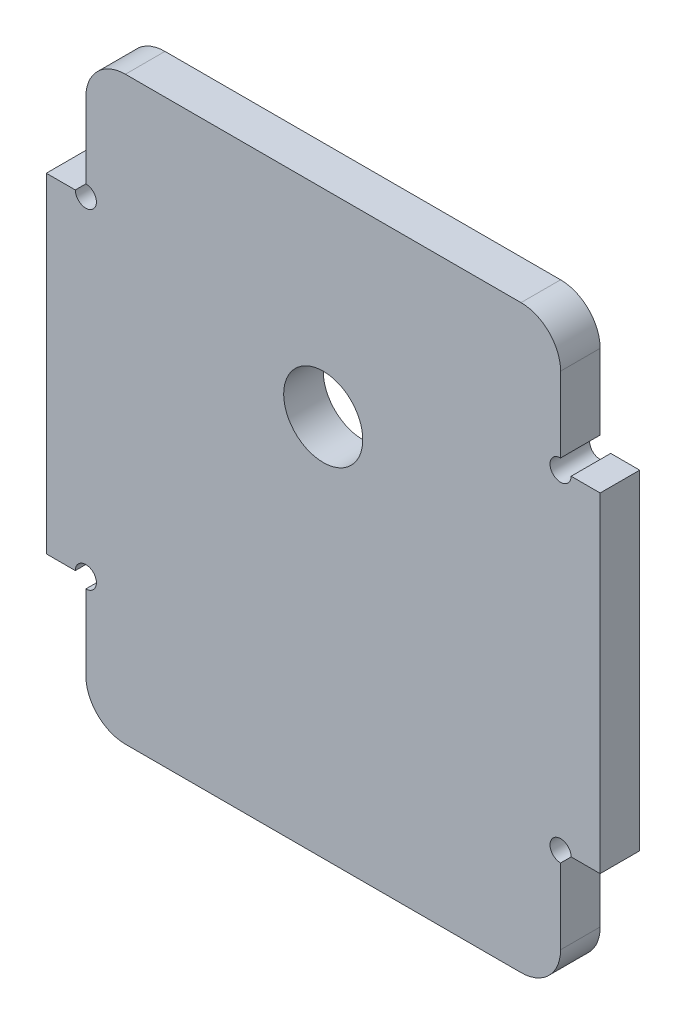
SolidWorks part; units mm, degrees
material "Thornel Mat VMA"
ref_plane "Front Plane" through (0, 0, 0) normal (0, 0, 1) x (1, 0, 0)
ref_plane "Top Plane" through (0, 0, 0) normal (0, 1, 0) x (1, 0, 0)
ref_plane "Right Plane" through (0, 0, 0) normal (1, 0, 0) x (0, 0, -1)
sketch "Sketch1" plane through (0, 0, 0) normal (0, 0, 1) x (1, 0, 0)
  line L0 (0, 0) -> (0, 22) construction
  line L1 (-18, -22) -> (18, -22)
  line L2 (-18, -22) -> (-18, 22)
  line L3 (-18, 22) -> (18, 22)
  line L4 (18, -22) -> (18, 22)
  line L5 (-18, -22) -> (18, 22) construction
  line L6 (-18, 22) -> (18, -22) construction
  line L7 (-21, -12.5) -> (-15, -12.5)
  line L8 (-21, -12.5) -> (-21, 12.5)
  line L9 (-21, 12.5) -> (-15, 12.5)
  line L10 (-15, -12.5) -> (-15, 12.5)
  line L11 (-21, -12.5) -> (-15, 12.5) construction
  line L12 (-21, 12.5) -> (-15, -12.5) construction
  line L13 (21, 12.5) -> (15, -12.5) construction
  line L14 (21, -12.5) -> (15, 12.5) construction
  line L15 (15, -12.5) -> (15, 12.5)
  line L16 (21, 12.5) -> (15, 12.5)
  line L17 (21, -12.5) -> (21, 12.5)
  line L18 (21, -12.5) -> (15, -12.5)
  point P0 (0, 0)
  point P6 (-18, 0)
  point P17 (18, 0)
  dimension "D1" = 36
  dimension "D2" = 44
  dimension "D3" = 6
  dimension "D4" = 25
extrude "Boss-Extrude1" add sketch "Sketch1" along normal blind 3 contours L4 L18 L15 L16 L3 L2 L9 L10 L7 L1 | L9 L8 L7 L2 | L7 L10 L9 L2 | L18 L17 L16 L4 | L18 L4 L16 L15
sketch "Sketch3" plane through (0, 0, 0) normal (0, 0, -1) x (-1, 0, 0)
  line L0 (18, 12.5) -> (18, 22) construction
  line L1 (-18, 22) -> (18, 22)
  line L2 (-18, 22) -> (-18, 42)
  line L3 (-18, 42) -> (18, 42)
  line L4 (18, 22) -> (18, 42)
  dimension "D1" = 20
sketch "Sketch5" plane through (0, 0, 0) normal (0, 0, -1) x (-1, 0, 0)
  line L0 (0, 22) -> (0, 7) construction
  line L1 (-18, 22) -> (18, 22) construction
  circle A0 centre (0, 7) radius 3
  dimension "D1" = 6
  dimension "D2" = 15
extrude "Cut-Extrude3" cut sketch "Sketch5" against normal through all
sketch "Sketch6" plane through (0, 0, 0) normal (0, 0, -1) x (-1, 0, 0)
  circle A0 centre (-18, 12.5) radius 0.8
  circle A1 centre (-18, -12.5) radius 0.8
  circle A2 centre (18, -12.5) radius 0.8
  circle A3 centre (18, 12.5) radius 0.8
  dimension "D1" = 1.6
extrude "Cut-Extrude4" cut sketch "Sketch6" against normal through all
fillet "Fillet1" radius 3 4 edges at (18, -22, 1.5) (-18, -22, 1.5) (-18, 22, 1.5) (18, 22, 1.5)
